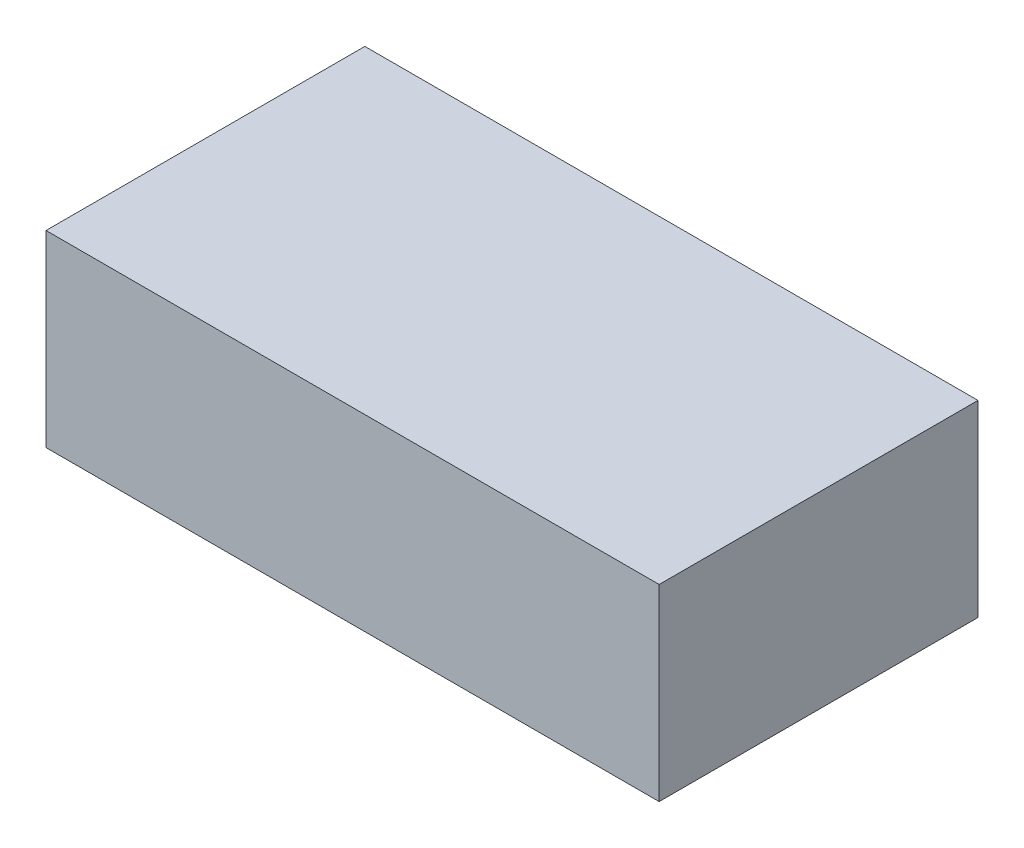
SolidWorks part; units mm, degrees
ref_plane "Front Plane" through (0, 0, 0) normal (0, 0, 1) x (1, 0, 0)
ref_plane "Top Plane" through (0, 0, 0) normal (0, 1, 0) x (1, 0, 0)
ref_plane "Right Plane" through (0, 0, 0) normal (1, 0, 0) x (0, 0, -1)
sketch "Sketch1" plane through (0, 0, 0) normal (0, 0, 1) x (1, 0, 0)
  line L1 (0, 0) -> (75, 0)
  line L2 (0, 0) -> (0, 23)
  line L3 (0, 23) -> (75, 23)
  line L4 (75, 0) -> (75, 23)
  dimension "D1" = 75
  dimension "D2" = 23
extrude "Profile" add sketch "Sketch1" along normal blind 39
equation "\"Profile_Depth\"= 39mm"
equation "\"D1@Profile\" = \"Profile_Depth\""
equation "\"Profile_Sketch_1\"= 75mm"
equation "\"D1@Sketch1\" = \"Profile_Sketch_1\""
equation "\"Profile_Sketch_2\"= 23mm"
equation "\"D2@Sketch1\" = \"Profile_Sketch_2\""
equation "\"EnvelopeWidth\"= 75mm"
equation "\"EnvelopeHeight\"= 23mm"
